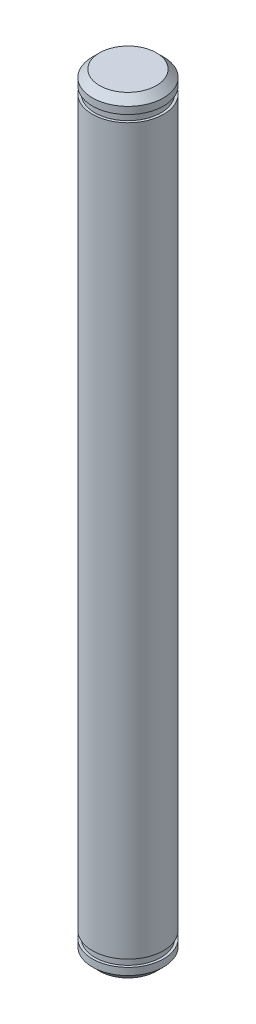
SolidWorks part; units mm, degrees
ref_plane "前视基准面" through (0, 0, 0) normal (0, 0, 1) x (1, 0, 0)
ref_plane "上视基准面" through (0, 0, 0) normal (0, 1, 0) x (1, 0, 0)
ref_plane "右视基准面" through (0, 0, 0) normal (1, 0, 0) x (0, 0, -1)
other "Configuration Table"
sketch "草图1" plane through (0, 0, 0) normal (0, 0, 1) x (1, 0, 0)
  line L0 (0, 17.9143) -> (0, -10.0949) construction
  line L1 (0, 54) -> (5, 54)
  line L2 (5, 54) -> (5, 30)
  line L4 (5, 30) -> (5, -30)
  line L6 (5, -30) -> (5, -54)
  line L7 (5, -54) -> (0, -54)
  line L8 (0, 0) -> (25.4592, 0) construction
  line L9 (0, 54) -> (0, -54)
  dimension "D1" = 5
  dimension "D3" = 60
  dimension "D4" = 24
  dimension "D5" = 24
revolve "旋转1" add sketch "草图1" angle 360 about L9
chamfer "倒角1" distance 1 angle 45 2 edges at (-5, -54, 0) (-5, 54, 0)
ref_plane "基准面1" through (0, 0, 0) normal (0, 1, 0) x (1, 0, 0)
sketch "草图2" plane through (0, 54, 0) normal (0, 1, 0) x (1, 0, 0)
  circle A0 centre (0, 0) radius 4.65
  circle A1 centre (0, 0) radius 5 construction
  circle A2 centre (0, 0) radius 5
  dimension "D1" = 9.3
extrude "切除-拉伸1" cut sketch "草图2" along normal blind 1 from offset 3 offset against normal yes
mirror "镜向1" about plane through (0, 0, 0) normal (0, 1, 0) of "切除-拉伸1"
